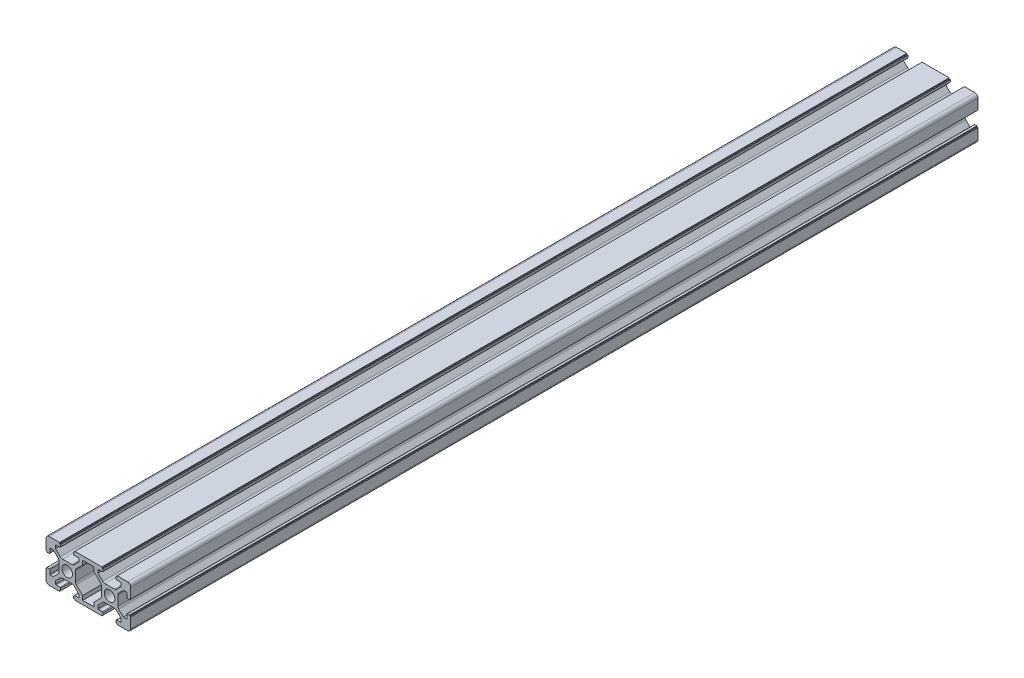
SolidWorks part; units mm, degrees
ref_plane "前视基准面" through (0, 0, 0) normal (0, 0, 1) x (1, 0, 0)
ref_plane "上视基准面" through (0, 0, 0) normal (0, 1, 0) x (1, 0, 0)
ref_plane "右视基准面" through (0, 0, 0) normal (1, 0, 0) x (0, 0, -1)
sketch "草图1" plane through (0, 0, 0) normal (0, 0, 1) x (1, 0, 0)
  line L0 (-1.9716, -6.6942) -> (-4.9322, -3.7335)
  line L1 (-5.3716, -2.6729) -> (-5.3716, 1.7645)
  line L2 (-4.9322, 2.8251) -> (-1.9716, 5.7858)
  line L3 (-0.7716, 9.5458) -> (-5.6716, 9.5458)
  line L4 (-5.6716, 9.5458) -> (-5.6716, 9.2458)
  line L5 (-5.8716, 9.0458) -> (-6.1716, 9.0458)
  line L6 (-6.1716, 9.0458) -> (-6.1716, 8.0458)
  line L7 (-5.8716, 7.7458) -> (-4.0716, 7.7458)
  line L8 (-3.7716, 7.4458) -> (-3.7716, 6.1058)
  line L9 (-3.7716, 6.1058) -> (-5.9922, 3.8851)
  line L10 (-7.0529, 3.4458) -> (-11.4903, 3.4458)
  line L11 (-12.5509, 3.8851) -> (-14.7716, 6.1058)
  line L12 (-14.7716, 6.1058) -> (-14.7716, 7.4458)
  line L13 (-14.4716, 7.7458) -> (-12.6716, 7.7458)
  line L14 (-12.3716, 8.0458) -> (-12.3716, 9.0458)
  line L15 (-12.3716, 9.0458) -> (-12.6716, 9.0458)
  line L16 (-12.8716, 9.2458) -> (-12.8716, 9.5458)
  line L17 (-12.8716, 9.5458) -> (-17.7716, 9.5458)
  line L18 (-19.2716, 8.0458) -> (-19.2716, 3.1458)
  line L19 (-19.2716, 3.1458) -> (-18.9716, 3.1458)
  line L20 (-18.7716, 2.9458) -> (-18.7716, 2.6458)
  line L21 (-18.7716, 2.6458) -> (-17.7716, 2.6458)
  line L22 (-17.4716, 2.9458) -> (-17.4716, 4.7458)
  line L23 (-17.1716, 5.0458) -> (-15.8316, 5.0458)
  line L24 (-15.8316, 5.0458) -> (-13.6109, 2.8251)
  line L25 (-13.1716, 1.7645) -> (-13.1716, -2.6729)
  line L26 (-13.6109, -3.7335) -> (-15.8316, -5.9542)
  line L27 (-15.8316, -5.9542) -> (-17.1716, -5.9542)
  line L28 (-17.4716, -5.6542) -> (-17.4716, -3.8542)
  line L29 (-17.7716, -3.5542) -> (-18.7716, -3.5542)
  line L30 (-18.7716, -3.5542) -> (-18.7716, -3.8542)
  line L31 (-18.9716, -4.0542) -> (-19.2716, -4.0542)
  line L32 (-19.2716, -4.0542) -> (-19.2716, -8.9542)
  line L33 (-17.7716, -10.4542) -> (-12.8716, -10.4542)
  line L34 (-12.8716, -10.4542) -> (-12.8716, -10.1542)
  line L35 (-12.6716, -9.9542) -> (-12.3716, -9.9542)
  line L36 (-12.3716, -9.9542) -> (-12.3716, -8.9542)
  line L37 (-12.6716, -8.6542) -> (-14.4716, -8.6542)
  line L38 (-14.7716, -8.3542) -> (-14.7716, -7.0142)
  line L39 (-14.7716, -7.0142) -> (-12.5509, -4.7935)
  line L40 (-11.4903, -4.3542) -> (-7.0529, -4.3542)
  line L41 (-5.9922, -4.7935) -> (-3.7716, -7.0142)
  line L42 (-3.7716, -7.0142) -> (-3.7716, -8.3542)
  line L43 (-4.0716, -8.6542) -> (-5.8716, -8.6542)
  line L44 (-6.1716, -8.9542) -> (-6.1716, -9.9542)
  line L45 (-6.1716, -9.9542) -> (-5.8716, -9.9542)
  line L46 (-5.6716, -10.1542) -> (-5.6716, -10.4542)
  line L47 (-5.6716, -10.4542) -> (-0.7716, -10.4542)
  line L48 (-0.7716, -10.4542) -> (7.1284, -10.4542)
  line L49 (7.1284, -10.4542) -> (7.1284, -10.1542)
  line L50 (7.3284, -9.9542) -> (7.6284, -9.9542)
  line L51 (7.6284, -9.9542) -> (7.6284, -8.9542)
  line L52 (7.3284, -8.6542) -> (5.5284, -8.6542)
  line L53 (5.2284, -8.3542) -> (5.2284, -7.0142)
  line L54 (5.2284, -7.0142) -> (7.4491, -4.7935)
  line L55 (8.5097, -4.3542) -> (12.9471, -4.3542)
  line L56 (14.0078, -4.7935) -> (16.2284, -7.0142)
  line L57 (16.2284, -7.0142) -> (16.2284, -8.3542)
  line L58 (15.9284, -8.6542) -> (14.1284, -8.6542)
  line L59 (13.8284, -8.9542) -> (13.8284, -9.9542)
  line L60 (13.8284, -9.9542) -> (14.1284, -9.9542)
  line L61 (14.3284, -10.1542) -> (14.3284, -10.4542)
  line L62 (14.3284, -10.4542) -> (19.2284, -10.4542)
  line L63 (20.7284, -8.9542) -> (20.7284, -4.0542)
  line L64 (20.7284, -4.0542) -> (20.4284, -4.0542)
  line L65 (20.2284, -3.8542) -> (20.2284, -3.5542)
  line L66 (20.2284, -3.5542) -> (19.2284, -3.5542)
  line L67 (18.9284, -3.8542) -> (18.9284, -5.6542)
  line L68 (18.6284, -5.9542) -> (17.2884, -5.9542)
  line L69 (17.2884, -5.9542) -> (15.0678, -3.7335)
  line L70 (14.6284, -2.6729) -> (14.6284, 1.7645)
  line L71 (15.0678, 2.8251) -> (17.2884, 5.0458)
  line L72 (17.2884, 5.0458) -> (18.6284, 5.0458)
  line L73 (18.9284, 4.7458) -> (18.9284, 2.9458)
  line L74 (19.2284, 2.6458) -> (20.2284, 2.6458)
  line L75 (20.2284, 2.6458) -> (20.2284, 2.9458)
  line L76 (20.4284, 3.1458) -> (20.7284, 3.1458)
  line L77 (20.7284, 3.1458) -> (20.7284, 8.0458)
  line L78 (19.2284, 9.5458) -> (14.3284, 9.5458)
  line L79 (14.3284, 9.5458) -> (14.3284, 9.2458)
  line L80 (14.1284, 9.0458) -> (13.8284, 9.0458)
  line L81 (13.8284, 9.0458) -> (13.8284, 8.0458)
  line L82 (14.1284, 7.7458) -> (15.9284, 7.7458)
  line L83 (16.2284, 7.4458) -> (16.2284, 6.1058)
  line L84 (16.2284, 6.1058) -> (14.0078, 3.8851)
  line L85 (12.9471, 3.4458) -> (8.5097, 3.4458)
  line L86 (7.4491, 3.8851) -> (5.2284, 6.1058)
  line L87 (5.2284, 6.1058) -> (5.2284, 7.4458)
  line L88 (5.5284, 7.7458) -> (7.3284, 7.7458)
  line L89 (7.6284, 8.0458) -> (7.6284, 9.0458)
  line L90 (7.6284, 9.0458) -> (7.3284, 9.0458)
  line L91 (7.1284, 9.2458) -> (7.1284, 9.5458)
  line L92 (7.1284, 9.5458) -> (2.2284, 9.5458)
  line L93 (3.4284, 5.7858) -> (6.3891, 2.8251)
  line L94 (6.8284, 1.7645) -> (6.8284, -2.6729)
  line L95 (6.3891, -3.7335) -> (3.4284, -6.6942)
  line L96 (-0.7716, 9.5458) -> (2.2284, 9.5458)
  line L99 (-1.9716, 7.7458) -> (3.4284, 7.7458)
  line L100 (3.4284, 7.7458) -> (3.4284, 5.7858)
  line L101 (-1.9716, 7.7458) -> (-1.9716, 5.7858)
  line L102 (-1.9716, -8.6542) -> (3.4284, -8.6542)
  line L103 (3.4284, -8.6542) -> (3.4284, -6.6942)
  line L104 (-1.9716, -8.6542) -> (-1.9716, -6.6942)
  arc A1 (-5.3716, -2.6729) -> (-4.9322, -3.7335) centre (-3.8716, -2.6729) ccw
  arc A2 (-4.9322, 2.8251) -> (-5.3716, 1.7645) centre (-3.8716, 1.7645) ccw
  arc A3 (-5.8716, 9.0458) -> (-5.6716, 9.2458) centre (-5.8716, 9.2458) ccw
  arc A4 (-6.1716, 8.0458) -> (-5.8716, 7.7458) centre (-5.8716, 8.0458) ccw
  arc A5 (-3.7716, 7.4458) -> (-4.0716, 7.7458) centre (-4.0716, 7.4458) ccw
  arc A6 (-7.0529, 3.4458) -> (-5.9922, 3.8851) centre (-7.0529, 4.9458) ccw
  arc A7 (-12.5509, 3.8851) -> (-11.4903, 3.4458) centre (-11.4903, 4.9458) ccw
  arc A8 (-14.4716, 7.7458) -> (-14.7716, 7.4458) centre (-14.4716, 7.4458) ccw
  arc A9 (-12.6716, 7.7458) -> (-12.3716, 8.0458) centre (-12.6716, 8.0458) ccw
  arc A10 (-12.8716, 9.2458) -> (-12.6716, 9.0458) centre (-12.6716, 9.2458) ccw
  arc A11 (-17.7716, 9.5458) -> (-19.2716, 8.0458) centre (-17.7716, 8.0458) ccw
  arc A12 (-18.7716, 2.9458) -> (-18.9716, 3.1458) centre (-18.9716, 2.9458) ccw
  arc A13 (-17.7716, 2.6458) -> (-17.4716, 2.9458) centre (-17.7716, 2.9458) ccw
  arc A14 (-17.1716, 5.0458) -> (-17.4716, 4.7458) centre (-17.1716, 4.7458) ccw
  arc A15 (-13.1716, 1.7645) -> (-13.6109, 2.8251) centre (-14.6716, 1.7645) ccw
  arc A16 (-13.6109, -3.7335) -> (-13.1716, -2.6729) centre (-14.6716, -2.6729) ccw
  arc A17 (-17.4716, -5.6542) -> (-17.1716, -5.9542) centre (-17.1716, -5.6542) ccw
  arc A18 (-17.4716, -3.8542) -> (-17.7716, -3.5542) centre (-17.7716, -3.8542) ccw
  arc A19 (-18.9716, -4.0542) -> (-18.7716, -3.8542) centre (-18.9716, -3.8542) ccw
  arc A20 (-19.2716, -8.9542) -> (-17.7716, -10.4542) centre (-17.7716, -8.9542) ccw
  arc A21 (-12.6716, -9.9542) -> (-12.8716, -10.1542) centre (-12.6716, -10.1542) ccw
  arc A22 (-12.3716, -8.9542) -> (-12.6716, -8.6542) centre (-12.6716, -8.9542) ccw
  arc A23 (-14.7716, -8.3542) -> (-14.4716, -8.6542) centre (-14.4716, -8.3542) ccw
  arc A24 (-11.4903, -4.3542) -> (-12.5509, -4.7935) centre (-11.4903, -5.8542) ccw
  arc A25 (-5.9922, -4.7935) -> (-7.0529, -4.3542) centre (-7.0529, -5.8542) ccw
  arc A26 (-4.0716, -8.6542) -> (-3.7716, -8.3542) centre (-4.0716, -8.3542) ccw
  arc A27 (-5.8716, -8.6542) -> (-6.1716, -8.9542) centre (-5.8716, -8.9542) ccw
  arc A28 (-5.6716, -10.1542) -> (-5.8716, -9.9542) centre (-5.8716, -10.1542) ccw
  arc A29 (7.3284, -9.9542) -> (7.1284, -10.1542) centre (7.3284, -10.1542) ccw
  arc A30 (7.6284, -8.9542) -> (7.3284, -8.6542) centre (7.3284, -8.9542) ccw
  arc A31 (5.2284, -8.3542) -> (5.5284, -8.6542) centre (5.5284, -8.3542) ccw
  arc A32 (8.5097, -4.3542) -> (7.4491, -4.7935) centre (8.5097, -5.8542) ccw
  arc A33 (14.0078, -4.7935) -> (12.9471, -4.3542) centre (12.9471, -5.8542) ccw
  arc A34 (15.9284, -8.6542) -> (16.2284, -8.3542) centre (15.9284, -8.3542) ccw
  arc A35 (14.1284, -8.6542) -> (13.8284, -8.9542) centre (14.1284, -8.9542) ccw
  arc A36 (14.3284, -10.1542) -> (14.1284, -9.9542) centre (14.1284, -10.1542) ccw
  arc A37 (19.2284, -10.4542) -> (20.7284, -8.9542) centre (19.2284, -8.9542) ccw
  arc A38 (20.2284, -3.8542) -> (20.4284, -4.0542) centre (20.4284, -3.8542) ccw
  arc A39 (19.2284, -3.5542) -> (18.9284, -3.8542) centre (19.2284, -3.8542) ccw
  arc A40 (18.6284, -5.9542) -> (18.9284, -5.6542) centre (18.6284, -5.6542) ccw
  arc A41 (14.6284, -2.6729) -> (15.0678, -3.7335) centre (16.1284, -2.6729) ccw
  arc A42 (15.0678, 2.8251) -> (14.6284, 1.7645) centre (16.1284, 1.7645) ccw
  arc A43 (18.9284, 4.7458) -> (18.6284, 5.0458) centre (18.6284, 4.7458) ccw
  arc A44 (18.9284, 2.9458) -> (19.2284, 2.6458) centre (19.2284, 2.9458) ccw
  arc A45 (20.4284, 3.1458) -> (20.2284, 2.9458) centre (20.4284, 2.9458) ccw
  arc A46 (20.7284, 8.0458) -> (19.2284, 9.5458) centre (19.2284, 8.0458) ccw
  arc A47 (14.1284, 9.0458) -> (14.3284, 9.2458) centre (14.1284, 9.2458) ccw
  arc A48 (13.8284, 8.0458) -> (14.1284, 7.7458) centre (14.1284, 8.0458) ccw
  arc A49 (16.2284, 7.4458) -> (15.9284, 7.7458) centre (15.9284, 7.4458) ccw
  arc A50 (12.9471, 3.4458) -> (14.0078, 3.8851) centre (12.9471, 4.9458) ccw
  arc A51 (7.4491, 3.8851) -> (8.5097, 3.4458) centre (8.5097, 4.9458) ccw
  arc A52 (5.5284, 7.7458) -> (5.2284, 7.4458) centre (5.5284, 7.4458) ccw
  arc A53 (7.3284, 7.7458) -> (7.6284, 8.0458) centre (7.3284, 8.0458) ccw
  arc A54 (7.1284, 9.2458) -> (7.3284, 9.0458) centre (7.3284, 9.2458) ccw
  arc A55 (6.8284, 1.7645) -> (6.3891, 2.8251) centre (5.3284, 1.7645) ccw
  arc A56 (6.3891, -3.7335) -> (6.8284, -2.6729) centre (5.3284, -2.6729) ccw
  circle A58 centre (10.7284, -0.4542) radius 2.5
  circle A63 centre (-9.2716, -0.4542) radius 2.5
extrude "凸台-拉伸1" add sketch "草图1" along normal blind 400
